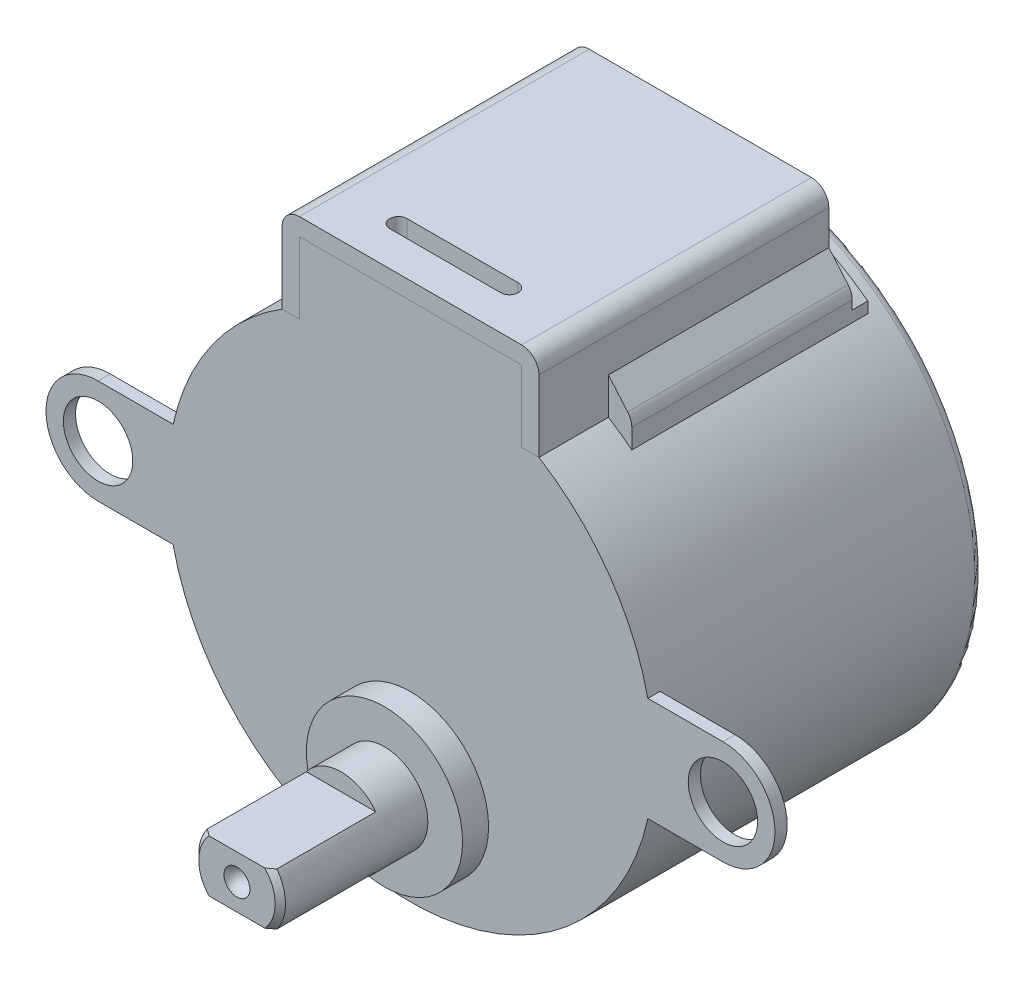
SolidWorks part; units mm, degrees
ref_plane "Ön Düzlem" through (0, 0, 0) normal (0, 0, 1) x (1, 0, 0)
ref_plane "Üst Düzlem" through (0, 0, 0) normal (0, 1, 0) x (1, 0, 0)
ref_plane "Sağ Düzlem" through (0, 0, 0) normal (1, 0, 0) x (0, 0, -1)
sketch "Çizim1" plane through (0, 0, 0) normal (0, 0, 1) x (1, 0, 0)
  circle A0 centre (0, 0) radius 14
  dimension "D1" = 28
extrude "Yükseklik-Ekstrüzyon1" add sketch "Çizim1" along normal blind 19
sketch "Çizim2" plane through (0, 0, 19) normal (0, 0, 1) x (1, 0, 0)
  line L0 (0, 14) -> (0, 8) construction
  circle A0 centre (0, 0) radius 14 construction
  circle A1 centre (0, 8) radius 4.5
  dimension "D2" = 9
  dimension "D1" = 6
extrude "Yükseklik-Ekstrüzyon2" add sketch "Çizim2" along normal blind 1.5
sketch "Çizim3" plane through (0, 0, 20.5) normal (0, 0, 1) x (1, 0, 0)
  circle A0 centre (0, 8) radius 2.5
  dimension "D1" = 5
extrude "Yükseklik-Ekstrüzyon3" add sketch "Çizim3" along normal blind 8.5
sketch "Çizim4" plane through (0, 0, 29) normal (0, 0, 1) x (1, 0, 0)
  line L0 (0, 10.5) -> (0, 9.5) construction
  line L1 (0, 9.5) -> (2.1768, 9.5)
  line L2 (2.1768, 9.5) -> (2.1768, 10.5)
  line L3 (2.1768, 10.5) -> (-2.3997, 10.5)
  line L4 (-2.3997, 10.5) -> (-2.3997, 9.5)
  line L5 (-2.3997, 9.5) -> (0, 9.5)
  line L6 (0, 8) -> (1.2994, 8) construction
  line L7 (2.1768, 5.5) -> (-2.3997, 5.5)
  line L8 (2.1768, 6.5) -> (2.1768, 5.5)
  line L9 (-2.3997, 5.5) -> (-2.3997, 6.5)
  line L10 (-2.3997, 6.5) -> (0, 6.5)
  line L11 (0, 6.5) -> (2.1768, 6.5)
  circle A0 centre (0, 8) radius 2.5 construction
  circle A1 centre (0, 8) radius 2.5 construction
  dimension "D1" = 1
extrude "Kes-Ekstrüzyon1" cut sketch "Çizim4" against normal blind 6
chamfer "Pah1" distance 0.3 angle 45 2 edges at (-2.5, 8, 29) (2.5, 8, 29)
sketch "Çizim5" plane through (0, 0, 29) normal (0, 0, 1) x (1, 0, 0)
  line L0 (0, 8.75) -> (0, 7.25) construction
  line L1 (0, 8.75) -> (0, 7.25)
  arc A0 (0, 7.25) -> (0, 8.75) centre (0, 8) ccw
  dimension "D1" = 1.5
revolve "Kes-Döndür1" cut sketch "Çizim5" angle 360 about L0
sketch "Çizim6" plane through (0, 0, 19) normal (0, 0, 1) x (1, 0, 0)
  line L0 (0, 0) -> (0, -17) construction
  line L1 (0, -17) -> (7.4, -17)
  line L2 (7.4, -17) -> (7.4, -11.8844)
  line L4 (-7.4, -11.8844) -> (-7.4, -17)
  line L5 (-7.4, -17) -> (0, -17)
  arc A0 (-7.4, -11.8844) -> (7.4, -11.8844) centre (0, 0) ccw
  dimension "D1" = 17
  dimension "D2" = 7.4
  dimension "D3" = 7.4
extrude "Yükseklik-Ekstrüzyon4" add sketch "Çizim6" against normal blind 16.7
fillet "Radyus2" radius 1 2 edges at (7.4, -17, 10.65) (-7.4, -17, 10.65)
sketch "Çizim7" plane through (0, 0, 2.3) normal (0, 0, -1) x (-1, 0, 0)
  line L0 (7.4, -14) -> (7.4, -10.9287)
  line L1 (7.4, -11.8844) -> (7.4, -16) construction
  line L2 (7.4, -14) -> (8.75, -14) construction
  line L3 (8.75, -10.9287) -> (8.75, -12.0582)
  line L4 (7.4, -14) -> (8.5085, -12.7098)
  line L5 (7.4, -10.9287) -> (8.75, -10.9287)
  line L6 (0, -17) -> (0, -15.0954) construction
  line L7 (6.4, -17) -> (-6.4, -17) construction
  line L8 (-7.4, -14) -> (-7.4, -10.9287)
  line L9 (-7.4, -10.9287) -> (-8.75, -10.9287)
  line L10 (-8.75, -10.9287) -> (-8.75, -12.0582)
  line L11 (-7.4, -14) -> (-8.5085, -12.7098)
  circle A1 centre (0, 0) radius 14 construction
  arc A2 (8.75, -12.0582) -> (8.5085, -12.7098) centre (7.75, -12.0582) cw
  arc A3 (-8.75, -12.0582) -> (-8.5085, -12.7098) centre (-7.75, -12.0582) ccw
  point P21 (8.75, -12.4287)
  point P24 (-8.75, -12.4287)
  dimension "D1" = 1
  dimension "D2" = 1.35
  dimension "D3" = 1.5
extrude "Yükseklik-Ekstrüzyon5" add sketch "Çizim7" against normal blind 12.7
sketch "Çizim8" plane through (0, 0, 2.3) normal (0, 0, -1) x (-1, 0, 0)
  line L0 (-8.75, -10.9287) -> (-8.75, -11.5623)
  line L1 (8.75, -10.9287) -> (8.75, -11.5623)
  line L4 (1.5, -14.4222) -> (1.5, -13.9194)
  line L5 (-1.5, -14.4222) -> (-1.5, -13.9194)
  arc A0 (-8.75, -11.5623) -> (-1.5, -14.4222) centre (0, 0) ccw
  arc A1 (-8.75, -10.9287) -> (-1.5, -13.9194) centre (0, 0) ccw
  arc A2 (1.5, -13.9194) -> (8.75, -10.9287) centre (0, 0) ccw
  arc A3 (1.5, -14.4222) -> (8.75, -11.5623) centre (0, 0) ccw
  dimension "D1" = 29
extrude "Yükseklik-Ekstrüzyon6" add sketch "Çizim8" along normal blind 0.9
sketch "Çizim9" plane through (0, -17, 0) normal (0, -1, 0) x (1, 0, 0)
  line L0 (0, 19) -> (0, 17) construction
  line L1 (-6.4, 19) -> (6.4, 19) construction
  line L2 (0, 17) -> (3.2, 17) construction
  line L3 (3.2, 17) -> (3.2, 16) construction
  line L4 (3.2, 17) -> (-3.2, 17)
  line L6 (-3.2, 16) -> (3.2, 16)
  arc A0 (3.2, 16) -> (3.2, 17) centre (3.2, 16.5) ccw
  arc A1 (-3.2, 17) -> (-3.2, 16) centre (-3.2, 16.5) ccw
  dimension "D1" = 2
  dimension "D2" = 3.2
  dimension "D3" = 1
  dimension "D4" = 6.4
  dimension "D5" = 6.4
extrude "Kes-Ekstrüzyon2" cut sketch "Çizim9" against normal blind 2.3
fillet "Radyus3" radius 0.5 1 edges at (14, 0, 0)
sketch "Çizim10" plane through (0, 0, 19) normal (0, 0, 1) x (1, 0, 0)
  line L0 (0, 0) -> (0, -3) construction
  line L1 (0, -3) -> (18, -3) construction
  line L2 (18, 3) -> (13.6748, 3)
  line L3 (18, -3) -> (13.6748, -3)
  line L4 (-18, -3) -> (-13.6748, -3)
  line L5 (-18, 3) -> (-13.6748, 3)
  arc A0 (18, -3) -> (18, 3) centre (18, 0) ccw
  circle A1 centre (18, 0) radius 2
  arc A2 (7.4, -11.8844) -> (-7.4, -11.8844) centre (0, 0) ccw construction
  arc A3 (13.6748, -3) -> (13.6748, 3) centre (0, 0) ccw
  arc A4 (-13.6748, -3) -> (-13.6748, 3) centre (0, 0) cw
  circle A5 centre (-18, 0) radius 2
  arc A6 (-18, -3) -> (-18, 3) centre (-18, 0) cw
  dimension "D3" = 4
  dimension "D1" = 3
  dimension "D2" = 18
extrude "Yükseklik-Ekstrüzyon7" add sketch "Çizim10" against normal blind 0.7
sketch "Çizim11" plane through (0, 0, 0) normal (0, 0, -1) x (-1, 0, 0)
  text T0 "28BYJ-48"
extrude "Kes-Ekstrüzyon3" cut sketch "Çizim11" against normal blind 0.3
sketch "Çizim12" plane through (0, 0, 19) normal (0, 0, 1) x (1, 0, 0)
  line L0 (-7.4, -11.8844) -> (-6.4, -11.8844)
  line L1 (-6.4, -11.8844) -> (-6.4, -16)
  line L2 (-6.4, -16) -> (6.4, -16)
  line L3 (6.4, -16) -> (6.4, -11.8844)
  line L4 (6.4, -11.8844) -> (7.4, -11.8844)
  line L5 (7.4, -11.8844) -> (7.4, -16)
  line L6 (6.4, -17) -> (-6.4, -17)
  line L7 (-7.4, -16) -> (-7.4, -11.8844)
  arc A0 (6.4, -17) -> (7.4, -16) centre (6.4, -16) ccw construction
  arc A1 (7.4, -16) -> (6.4, -17) centre (6.4, -16) cw
  arc A2 (-6.4, -17) -> (-7.4, -16) centre (-6.4, -16) cw
extrude "Yükseklik-Ekstrüzyon8" add sketch "Çizim12" along normal blind 0.001
move or copy body "Body-Move/Copy1" bodies to move or copy 112 copy no rotation origin (0, -1.5, 0) rotation axis (0, 0, 1) rotation angle 179.5
move or copy body "Body-Move/Copy2" bodies to move or copy 113 copy no rotation origin (-0.0131, -1.4723, 0) rotation axis (0, 0, 1) rotation angle 0.5
